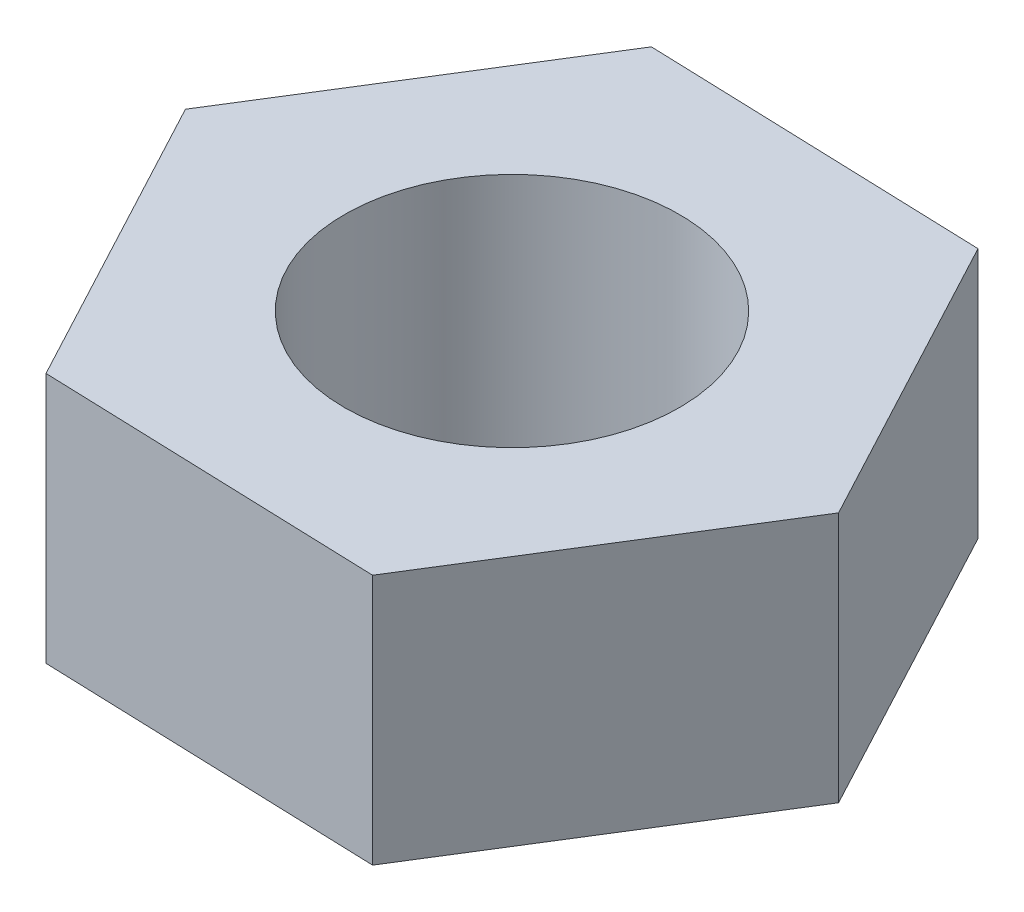
SolidWorks part; units mm, degrees
ref_plane "前视基准面" through (0, 0, 0) normal (0, 0, 1) x (1, 0, 0)
ref_plane "上视基准面" through (0, 0, 0) normal (0, 1, 0) x (1, 0, 0)
ref_plane "右视基准面" through (0, 0, 0) normal (1, 0, 0) x (0, 0, -1)
sketch "草图1" plane through (0, 0, 0) normal (0, 1, 0) x (1, 0, 0)
  line L1 (2.1384, 3.4294) -> (-1.9007, 3.5666)
  line L2 (-1.9007, 3.5666) -> (-4.0391, 0.1372)
  line L3 (-4.0391, 0.1372) -> (-2.1384, -3.4294)
  line L4 (-2.1384, -3.4294) -> (1.9007, -3.5666)
  line L5 (1.9007, -3.5666) -> (4.0391, -0.1372)
  line L6 (4.0391, -0.1372) -> (2.1384, 3.4294)
  circle A1 centre (0, 0) radius 3.5 construction
  dimension "D1" = 7
extrude "凸台-拉伸1" add sketch "草图1" along normal blind 3 contours L6 L1 L2 L3 L4 L5
sketch "草图2" plane through (0, 3, 0) normal (0, 1, 0) x (1, 0, 0)
  line L0 (2.1384, 3.4294) -> (-1.9007, 3.5666) construction
  circle A0 centre (0, 0) radius 3.5
extrude "凸台-拉伸2" add sketch "草图2" along normal blind 1
sketch "草图4" plane through (0, 4, 0) normal (0, 1, 0) x (1, 0, 0)
  circle A0 centre (0, 0) radius 2
  dimension "D1" = 4
extrude "切除-拉伸1" cut sketch "草图4" against normal through all
cosmetic thread "装饰螺纹线1" parameters "D2"=6
sketch "草图5" plane through (0, 3, 0) normal (0, 1, 0) x (1, 0, 0)
  line L6 (1.9007, -3.5666) -> (4.0391, -0.1372)
  line L7 (-2.1384, -3.4294) -> (1.9007, -3.5666)
  line L8 (-4.0391, 0.1372) -> (-2.1384, -3.4294)
  line L9 (-1.9007, 3.5666) -> (-4.0391, 0.1372)
  line L10 (2.1384, 3.4294) -> (-1.9007, 3.5666)
  line L11 (4.0391, -0.1372) -> (2.1384, 3.4294)
  line L12 (1.9007, -3.5666) -> (4.0391, -0.1372)
  line L13 (-2.1384, -3.4294) -> (1.9007, -3.5666)
  line L14 (-4.0391, 0.1372) -> (-2.1384, -3.4294)
  line L15 (-1.9007, 3.5666) -> (-4.0391, 0.1372)
  line L16 (2.1384, 3.4294) -> (-1.9007, 3.5666)
  line L17 (4.0391, -0.1372) -> (2.1384, 3.4294)
  dimension "D1" = 0
extrude "切除-拉伸2" cut sketch "草图5" along normal blind 10
